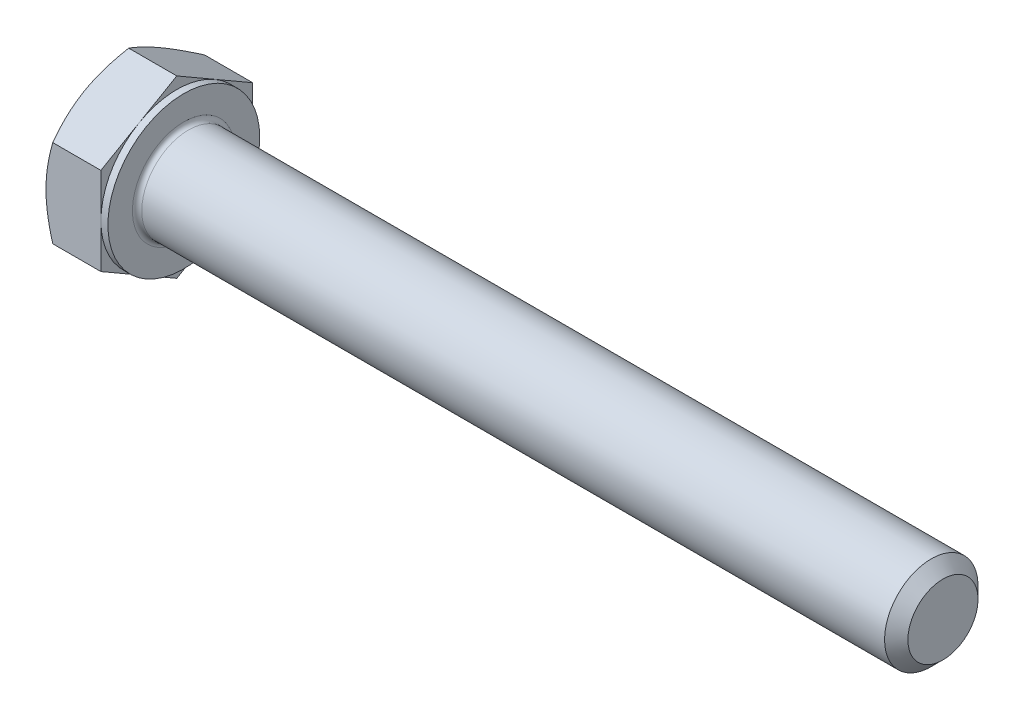
SolidWorks part; units mm, degrees
extrude "基体-拉伸" add sketch "草图1" along normal blind 5.3
sketch "草图1" plane through (0, 0, 0) normal (1, 0, 0) x (0, 0, -1)
  line L0 (6.5, 3.7528) -> (6.5, -3.7528)
  line L1 (-6.5, 3.7528) -> (-6.5, -3.7528)
  line L2 (6.5, -3.7528) -> (0, -7.5056)
  line L3 (0, -7.5056) -> (-6.5, -3.7528)
  line L4 (6.5, 3.7528) -> (0, 7.5056)
  line L5 (0, 7.5056) -> (-6.5, 3.7528)
  dimension "s" = 13
  dimension "D2" = 120
  dimension "D3" = 6.5
  dimension "D4" = 6.5
  dimension "D5" = 6.5
revolve "切除-旋转1" cut sketch "草图3" angle 360 about L6
sketch "草图3" plane through (0, 0, 0) normal (0, 0, 1) x (1, 0, 0)
  line L0 (0, 6.5) -> (3.4673, 12.5056)
  line L1 (0, 7.5056) -> (0, 3.7528) construction
  line L2 (3.4673, 12.5056) -> (3.4673, 17.5056)
  line L3 (3.4673, 17.5056) -> (-10, 17.5056)
  line L4 (-10, 17.5056) -> (-10, 6.5)
  line L5 (-10, 6.5) -> (0, 6.5)
  line L6 (0, 0) -> (99.06, 0) construction
  line L7 (5.3, 7.5056) -> (0, 7.5056) construction
  dimension "D1" = 6.5
  dimension "D2" = 5
  dimension "D3" = 10
  dimension "D4" = 5
  dimension "Head_ch_ang" = 30
material "Q235"
ref_plane "前视" through (0, 0, 0) normal (0, 0, 1) x (1, 0, 0)
ref_plane "上视" through (0, 0, 0) normal (0, 1, 0) x (1, 0, 0)
ref_plane "右视" through (0, 0, 0) normal (1, 0, 0) x (0, 0, -1)
sketch "草图2" plane through (0, 0, 0) normal (0, 0, 1) x (1, 0, 0)
  line L0 (0, 3.7528) -> (0, -3.7528) construction
  line L1 (0, 0) -> (70.3, 0)
  line L2 (0, 0) -> (0, 4)
  line L3 (0, 4) -> (7.7917, 4)
  line L4 (70.3, 0) -> (70.3, 2.9175)
  line L5 (5.3, 7.5056) -> (5.3, 3.7528) construction
  line L7 (0, 0) -> (96.52, 0) construction
  line L8 (70.3, -2.9175) -> (7.7917, -4) construction
  line L9 (0, -4) -> (7.7917, -4) construction
  line L10 (6.55, 15.24) -> (6.55, -1.27) construction
  line L11 (48.3, 15.24) -> (48.3, -1.27) construction
  line L12 (5.3, 3.7528) -> (5.3, -3.7528) construction
  line L13 (7.7917, 4) -> (70.3, 4)
  line L14 (70.3, 4) -> (70.3, 2.9175)
revolve "凸台-旋转1" add sketch "草图2" angle 360 about L7
cosmetic thread "螺旋线1" parameters "Thread_length"=22, "Thread_minor"=5.835
sketch "草图5" plane through (0, 0, 0) normal (0, 0, 1) x (1, 0, 0)
  line L0 (5.3, 6.5) -> (1.8327, 12.5056)
  line L1 (5.3, 7.5056) -> (5.3, 3.7528) construction
  line L2 (1.8327, 12.5056) -> (1.8327, 17.5056)
  line L3 (1.8327, 17.5056) -> (11.8327, 17.5056)
  line L4 (11.8327, 17.5056) -> (11.8327, 6.5)
  line L5 (11.8327, 6.5) -> (5.3, 6.5)
  line L7 (5.3, 7.5056) -> (0.5806, 7.5056) construction
  line L8 (0, 0) -> (99.06, 0) construction
  line L9 (0, 0) -> (99.06, 0) construction
  dimension "D1" = 6.5
  dimension "D2" = 5
  dimension "D3" = 10
  dimension "D4" = 5
  dimension "Head_ch_ang" = 30
revolve "切除-旋转2" cut sketch "草图5" angle 360 about L8
sketch "草图4" plane through (0, 0, 0) normal (0, 0, 1) x (1, 0, 0)
  line L1 (5.3, 7.5056) -> (5.3, 3.7528) construction
  line L2 (5.3, 6.5) -> (4.7, 6.5)
  line L3 (5.3, 6.5) -> (5.3, 17.5056)
  line L4 (5.3, 17.5056) -> (4.7, 17.5056)
  line L5 (0, 0) -> (95.25, 0) construction
  line L6 (0, 0) -> (96.52, 0) construction
  line L7 (4.7, 6.5) -> (4.7, 17.5056)
  line L8 (4.7194, 7.5056) -> (0.5806, 7.5056) construction
  dimension "D2" = 10
  dimension "D1" = 13
revolve "切除-旋转3" cut sketch "草图4" angle 360 about L5
chamfer "倒角" distance 1 angle 45 1 edges at (70.3, 0, 4)
fillet "圆角" radius 0.4 1 edges at (5.3, 0, -4)
sketch "草图6" plane through (0, 0, 0) normal (0, 0, 1) x (1, 0, 0)
  line L0 (48.3, -2.9175) -> (47.675, -4)
  line L1 (48.3, -2.9175) -> (48.925, -4)
  line L2 (48.925, -4) -> (48.925, -5)
  line L3 (-3.175, 0) -> (5.1513, 0) construction
  line L5 (48.925, -5) -> (47.675, -5)
  line L6 (47.675, -5) -> (47.675, -4)
  dimension "Thread_minor" = 5.835
  dimension "Diameter" = 8
  dimension "Start" = 48.3
revolve "切除-旋转4" [suppressed] cut sketch "草图6" angle 360 about L3
pattern_linear "阵列(线性)1" [suppressed]
equation "\"D3@草图1\" = \"s@草图1\" / 2"
equation "\"D4@草图1\" = \"D3@草图1\""
equation "\"D5@草图1\" = \"D4@草图1\""
equation "\"Thread_minor@螺旋线1\" = \"Minor_dia@草图2\""
equation "\"D1@草图3\" = \"s@草图1\" / 2"
equation "\"D1@草图5\" = \"s@草图1\" / 2"
equation "\"Head_ch_ang@草图5\" = \"Head_ch_ang@草图3\""
equation "\"D1@草图4\" = \"s@草图1\""
equation "\"Thread_length@螺旋线1\" = ((sgn( (\"l@草图2\" - \"p@草图2\" ) - \"h@草图2\" )-1)*( (\"l@草图2\" - \"p@草图2\" ) - \"h@草图2\" ))/-2+ \"h@草图2\""
equation "\"Thread_minor@草图6\" = \"Minor_dia@草图2\""
equation "\"Diameter@草图6\" = \"m@草图2\""
equation "\"Overcut@草图6\" = \"m@草图2\" * 1.25"
equation "\"Start@草图6\" = \"k@基体-拉伸\" + \"l@草图2\" - \"Thread_length@螺旋线1\"  '---Non-countersunk---"
equation "\"Num_threads@阵列(线性)1\" = int( \"Thread_length@螺旋线1\" / \"p@草图2\" + 0.999 )  + 1"
equation "\"Advance@阵列(线性)1\" = \"Thread_length@螺旋线1\" /  (\"Num_threads@阵列(线性)1\" - 1) 'relax it"
equation "\"Num_threads@阵列(线性)1\" = \"Num_threads@阵列(线性)1\" - sgn( \"Num_threads@阵列(线性)1\" - 1) '---chamfered tips only---"
equation "\"Minor_dia@草图2\" = \"m@草图2\"-\"p@草图2\" * 1.732"
equation "\"D1@倒角\" = \"p@草图2\"*0.8"
